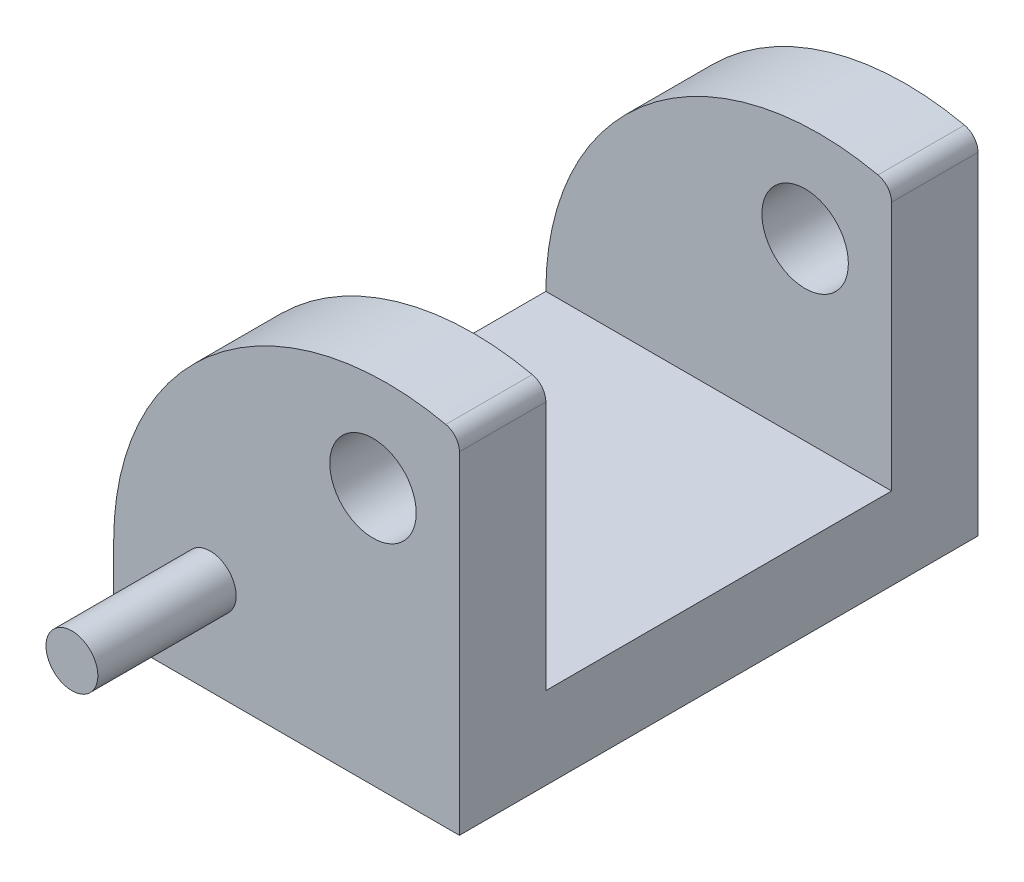
SolidWorks part; units mm, degrees
material "AISI 1020"
ref_plane "Front" through (0, 0, 0) normal (0, 0, 1) x (1, 0, 0)
ref_plane "Top" through (0, 0, 0) normal (0, 1, 0) x (1, 0, 0)
ref_plane "Right" through (0, 0, 0) normal (1, 0, 0) x (0, 0, -1)
sketch "Sketch1" plane through (0, 0, 0) normal (0, 0, 1) x (1, 0, 0)
  line L0 (-475.3365, 0) -> (32.6635, 0)
  line L1 (50, 0) -> (-50, 0) construction
  line L2 (32.6635, 0) -> (32.6635, 508)
  line L4 (-475.3365, 0) -> (-475.3365, 120.7391)
  arc A0 (-475.3365, 120.7391) -> (32.6635, 508) centre (-73.7273, 120.7391) cw
  circle A1 centre (-94.3365, 378.2913) radius 63.5
  dimension "D1" = 508
  dimension "D2" = 508
extrude "Boss-Extrude1" add sketch "Sketch1" along normal blind 762
ref_plane "Plane1" through (0, 508, 0) normal (0, 1, 0) x (1, 0, 0)
sketch "Sketch2" plane through (0, 508, 0) normal (0, 1, 0) x (1, 0, 0)
  line L1 (-556.0476, -127) -> (209.357, -127)
  line L2 (-556.0476, -127) -> (-556.0476, -635)
  line L3 (-556.0476, -635) -> (209.357, -635)
  line L4 (209.357, -127) -> (209.357, -635)
  dimension "D1" = 508
  dimension "D2" = 127
extrude "Cut-Extrude1" cut sketch "Sketch2" against normal up to vertex (387.2609 mm away) and the other way through all contours L2 L3 L4 L1
sketch "Sketch3" plane through (0, 0, 762) normal (0, 0, 1) x (1, 0, 0)
  circle A0 centre (-333.5077, 140.617) radius 38.1
  dimension "D1" = 76.2
extrude "Boss-Extrude2" add sketch "Sketch3" along normal blind 203.2
sketch "Sketch4" plane through (0, 120.7391, 0) normal (0, 1, 0) x (1, 0, 0)
  line L0 (-475.3365, -381) -> (32.6635, -381) construction
  line L1 (-475.3365, -635) -> (-475.3365, -127) construction
  line L2 (32.6635, -127) -> (32.6635, -635) construction
ref_plane "Plane2" through (0, 0, 381) normal (0, 0, 1) x (1, 0, 0)
mirror "Mirror1" about plane through (0, 0, 381) normal (0, 0, 1) of "Boss-Extrude2"
fillet "Fillet1" radius 25.4 2 edges at (32.6635, 508, 63.5) (32.6635, 508, 698.5)
